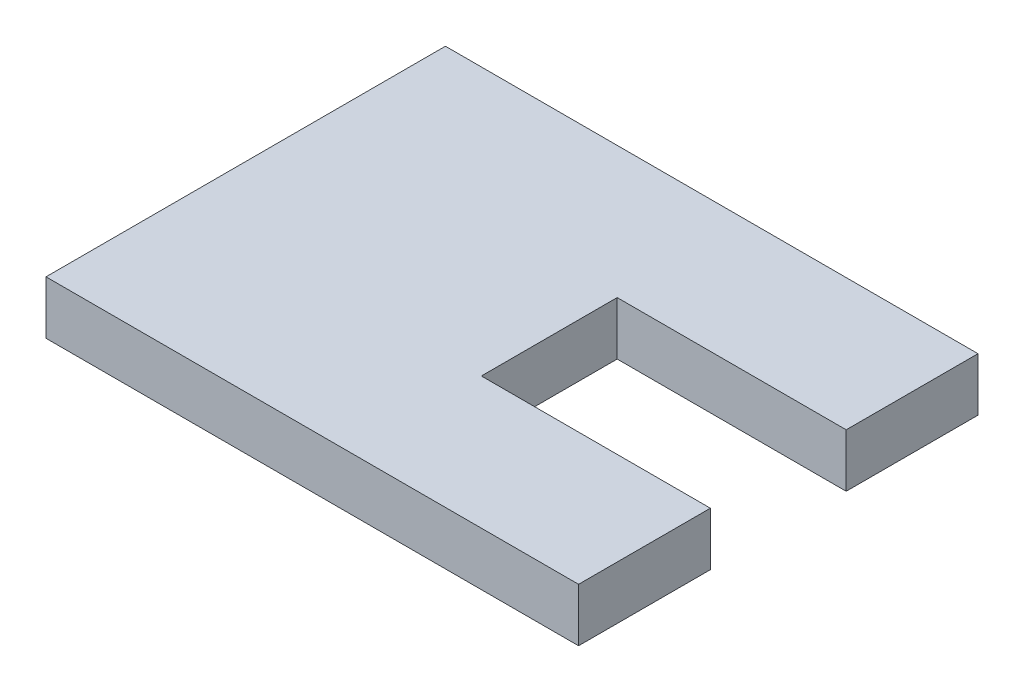
SolidWorks part; units mm, degrees
ref_plane "前基準面" through (0, 0, 0) normal (0, 0, 1) x (1, 0, 0)
ref_plane "上基準面" through (0, 0, 0) normal (0, 1, 0) x (1, 0, 0)
ref_plane "右基準面" through (0, 0, 0) normal (1, 0, 0) x (0, 0, -1)
sketch "草圖1" plane through (0, 0, 0) normal (0, 1, 0) x (1, 0, 0)
  line L1 (0, 0) -> (40, 0)
  line L2 (0, 0) -> (0, 30)
  line L3 (0, 30) -> (40, 30)
  line L4 (40, 0) -> (40, 30)
  dimension "D1" = 40
  dimension "D2" = 30
extrude "填料-伸長1" add sketch "草圖1" along normal blind 4
sketch "草圖2" plane through (0, 4, 0) normal (0, 1, 0) x (1, 0, 0)
  line L0 (40, 15) -> (0, 15) construction
  line L1 (40, 0) -> (40, 30) construction
  line L2 (0, 30) -> (0, 0) construction
  line L4 (40, 20.1) -> (17.8, 20.1)
  line L5 (40, 20.1) -> (40, 9.9)
  line L6 (40, 9.9) -> (17.8, 9.9)
  line L7 (17.8, 20.1) -> (17.8, 9.9)
  point P10 (40, 15)
  dimension "D1" = 10.2
  dimension "D2" = 22.2
extrude "除料-伸長1" cut sketch "草圖2" against normal blind 10 contours L4 L7 L6 L5
sketch "草圖3" plane through (17.8, 0, 0) normal (1, 0, 0) x (0, 0, -1)
  line L4 (9.9, 0) -> (20.1, 0)
  line L5 (20.1, 0) -> (20.1, 4)
  line L6 (20.1, 4) -> (9.9, 4)
  line L7 (9.9, 4) -> (9.9, 0)
  line L8 (9.9, 0) -> (20.1, 0)
  line L9 (20.1, 0) -> (20.1, 4)
  line L10 (20.1, 4) -> (9.9, 4)
  line L11 (9.9, 4) -> (9.9, 0)
  dimension "D1" = 0
extrude "填料-伸長2" add sketch "草圖3" along normal blind 5
